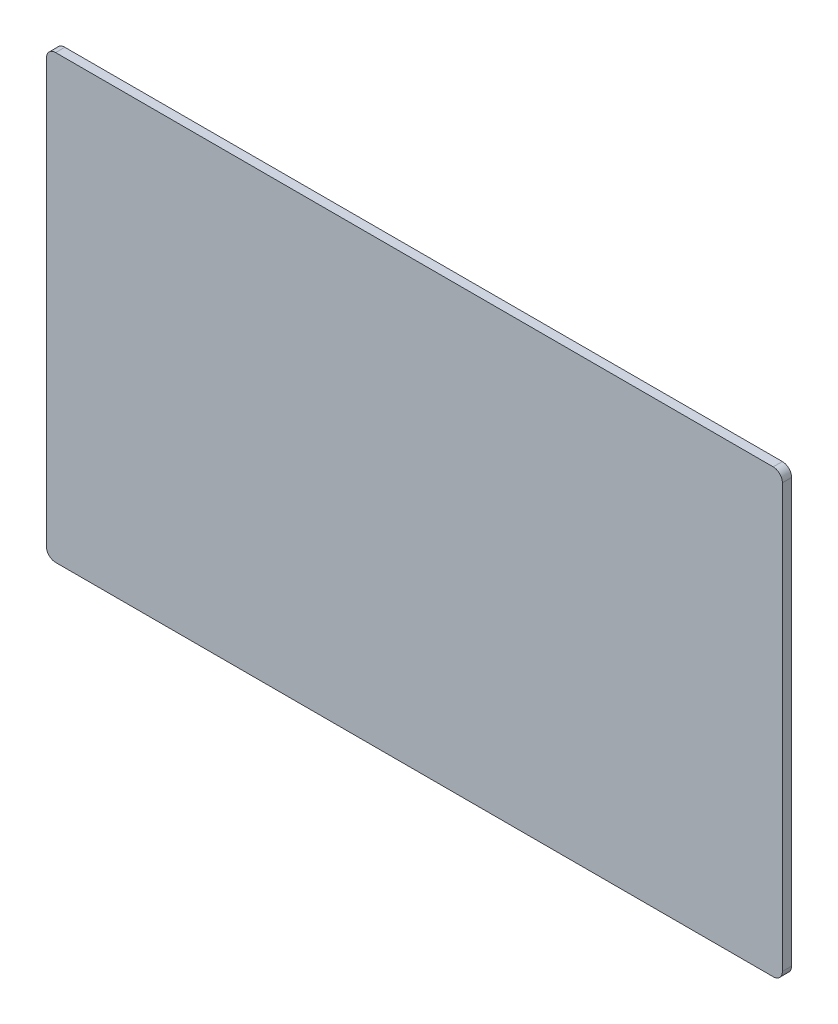
SolidWorks part; units mm, degrees
ref_plane "Front Plane" through (0, 0, 0) normal (0, 0, 1) x (1, 0, 0)
ref_plane "Top Plane" through (0, 0, 0) normal (0, 1, 0) x (1, 0, 0)
ref_plane "Right Plane" through (0, 0, 0) normal (1, 0, 0) x (0, 0, -1)
sketch "Sketch1" plane through (0, 0, 0) normal (0, 0, 1) x (1, 0, 0)
  line L1 (0, 0) -> (508, 0)
  line L2 (0, 0) -> (0, 304.8)
  line L3 (0, 304.8) -> (508, 304.8)
  line L4 (508, 0) -> (508, 304.8)
  dimension "D1" = 508
  dimension "D2" = 304.8
extrude "Boss-Extrude1" add sketch "Sketch1" along normal blind 6.35
fillet "Fillet1" radius 6.35 4 edges at (0, 304.8, 3.175) (508, 0, 3.175) (0, 0, 3.175) (508, 304.8, 3.175)
